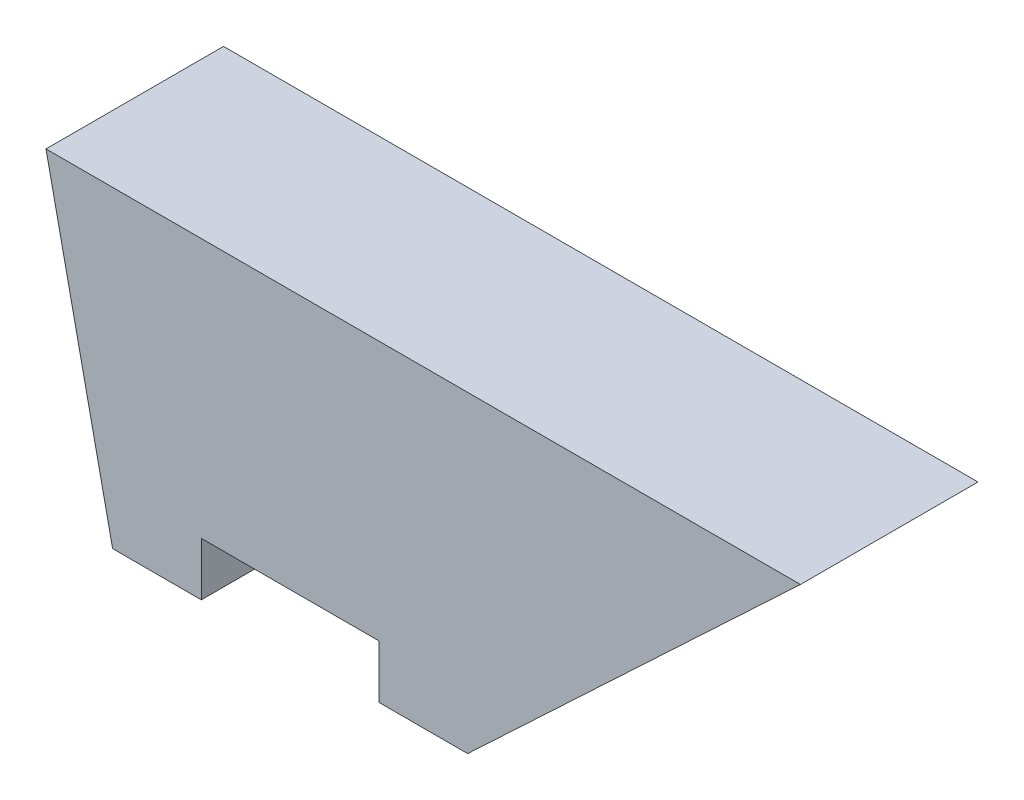
SolidWorks part; units mm, degrees
ref_plane "Piano frontale" through (0, 0, 0) normal (0, 0, 1) x (1, 0, 0)
ref_plane "Piano superiore" through (0, 0, 0) normal (0, 1, 0) x (1, 0, 0)
ref_plane "Piano destro" through (0, 0, 0) normal (1, 0, 0) x (0, 0, -1)
sketch "Schizzo1" plane through (0, 0, 0) normal (0, 0, 1) x (1, 0, 0)
  line L0 (-1.5, 7.05) -> (15.5, 7.05)
  line L4 (6, 0) -> (6, 1.2)
  line L5 (6, 1.2) -> (2, 1.2)
  line L6 (2, 1.2) -> (2, 0)
  line L7 (2, 0) -> (0, 0)
  line L8 (6, 0) -> (8, 0)
  line L9 (8, 0) -> (15.5, 7.05)
  line L10 (-1.5, 7.05) -> (0, 0)
  dimension "D1" = 4
  dimension "D2" = 1.2
  dimension "D3" = 5.85
  dimension "D4" = 2
  dimension "D5" = 2
  dimension "D6" = 17
  dimension "D7" = 7.5
extrude "Estrusione-Estrusione1" add sketch "Schizzo1" along normal blind 4
